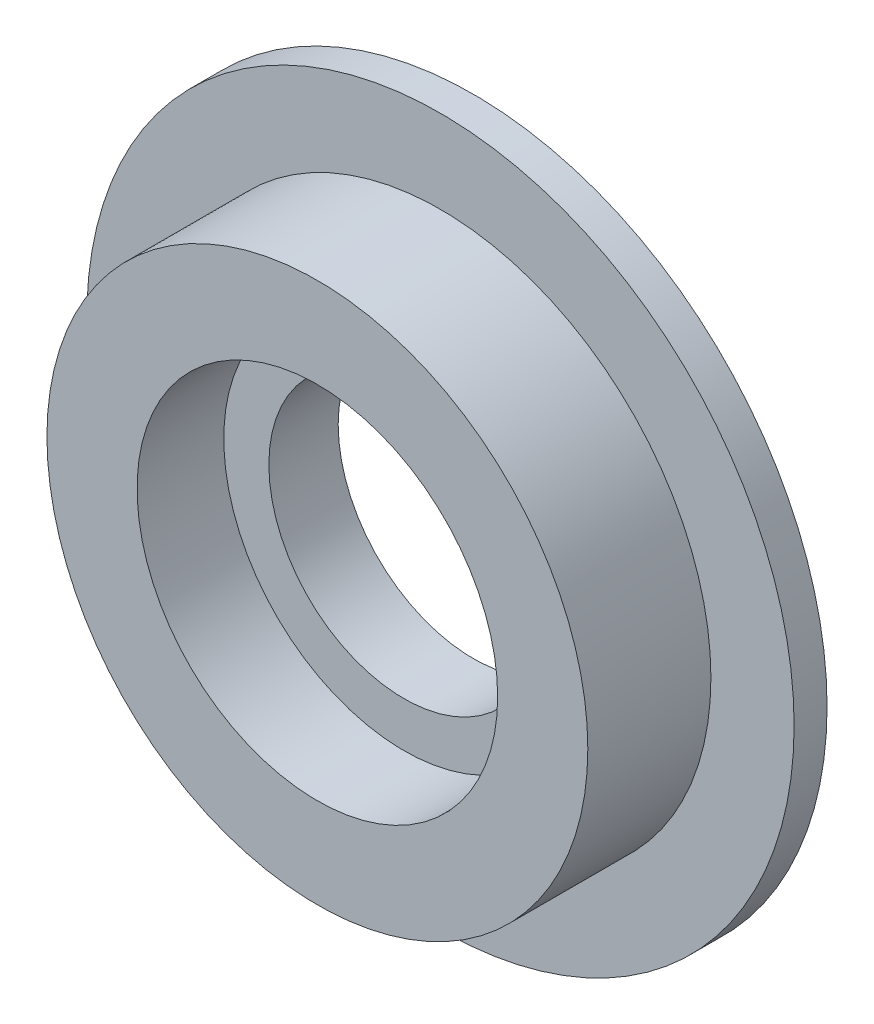
SolidWorks part; units mm, degrees
material "ABS"
ref_plane "Front Plane" through (0, 0, 0) normal (0, 0, 1) x (1, 0, 0)
ref_plane "Top Plane" through (0, 0, 0) normal (0, 1, 0) x (1, 0, 0)
ref_plane "Right Plane" through (0, 0, 0) normal (1, 0, 0) x (0, 0, -1)
ref_plane "Plane1" through (0, 0, 0.95) normal (0, 0, 1) x (1, 0, 0)
sketch "Sketch1" plane through (0, 0, 0.95) normal (0, 0, 1) x (1, 0, 0)
  circle A0 centre (0, 0) radius 10.2
  dimension "D1" = 20.4
extrude "Boss-Extrude1" add sketch "Sketch1" against normal blind 0.95
sketch "Sketch2" plane through (0, 0, 0.95) normal (0, 0, 1) x (1, 0, 0)
  circle A0 centre (0, 0) radius 7.8
  dimension "D1" = 15.6
extrude "Boss-Extrude2" add sketch "Sketch2" along normal blind 3.55
sketch "Sketch3" plane through (0, 0, 4.5) normal (0, 0, 1) x (1, 0, 0)
  circle A0 centre (0, 0) radius 5.2
  dimension "D1" = 10.4
extrude "Cut-Extrude1" cut sketch "Sketch3" against normal blind 2.5
sketch "Sketch4" plane through (0, 0, 0) normal (0, 0, -1) x (-1, 0, 0)
  circle A0 centre (0, 0) radius 3.9
  dimension "D1" = 7.8
extrude "Cut-Extrude2" cut sketch "Sketch4" against normal through all
